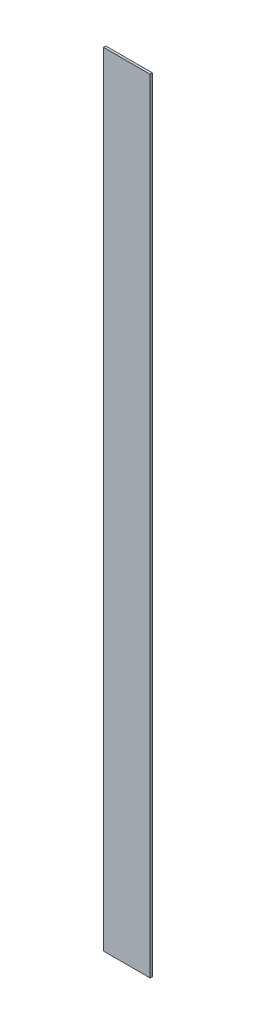
SolidWorks part; units mm, degrees
ref_plane "Front Plane" through (0, 0, 0) normal (0, 0, 1) x (1, 0, 0)
ref_plane "Top Plane" through (0, 0, 0) normal (0, 1, 0) x (1, 0, 0)
ref_plane "Right Plane" through (0, 0, 0) normal (1, 0, 0) x (0, 0, -1)
sketch "Sketch1" plane through (0, 0, 0) normal (1, 0, 0) x (0, 0, -1)
  line L9 (-0.254, 84) -> (0, 84)
  line L10 (-0.254, 84) -> (-0.254, 0)
  line L11 (-0.254, 0) -> (0, 0)
  line L12 (0, 84) -> (0, 0)
  dimension "BackingCard_Z" = 0.254
  dimension "BackingCard_Y" = 84
extrude "Boss-Extrude1" add sketch "Sketch1" along normal mid plane 5
